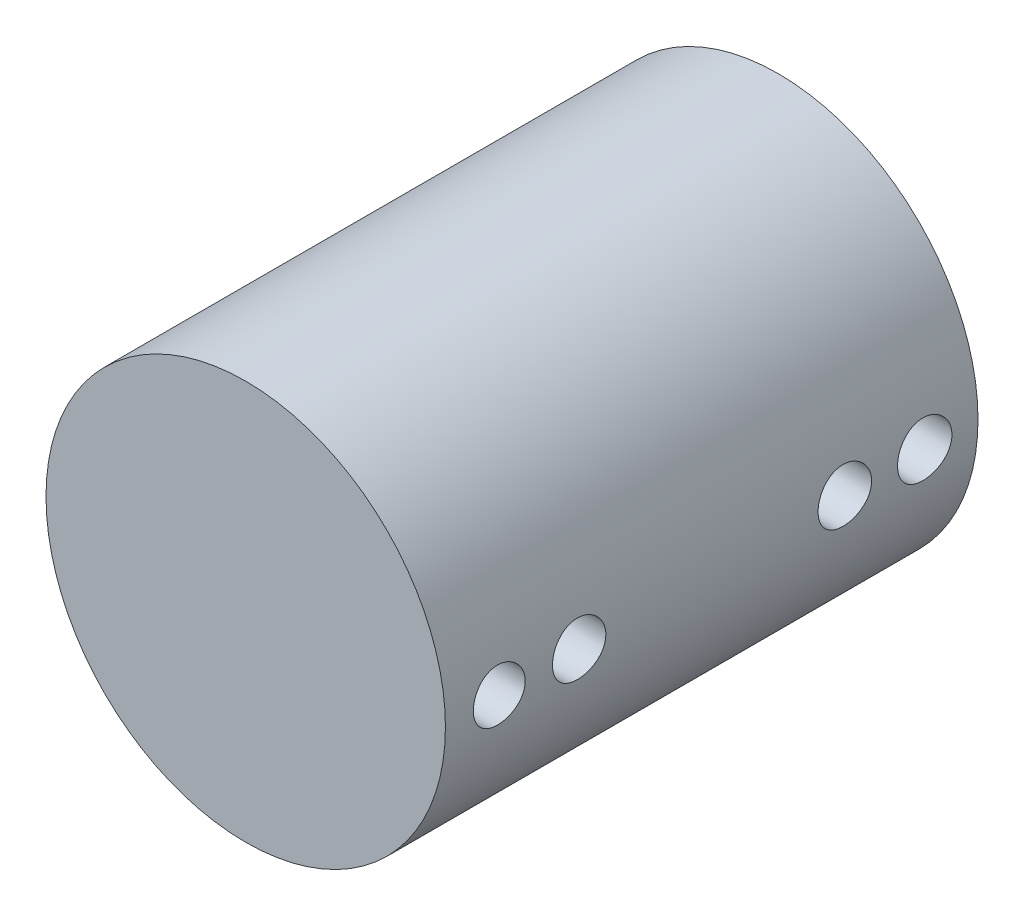
SolidWorks part; units mm, degrees
ref_plane "Front Plane" through (0, 0, 0) normal (0, 0, 1) x (1, 0, 0)
ref_plane "Top Plane" through (0, 0, 0) normal (0, 1, 0) x (1, 0, 0)
ref_plane "Right Plane" through (0, 0, 0) normal (1, 0, 0) x (0, 0, -1)
sketch "Sketch2" plane through (0, 0, 0) normal (0, 0, 1) x (1, 0, 0)
  circle A0 centre (0, 0) radius 19.05
extrude "Boss-Extrude1" add sketch "Sketch2" along normal blind 50.8
ref_plane "Plane1" through (-19.05, 0, 0) normal (-1, 0, 0) x (0, 0, 1)
sketch "Sketch3" plane through (-19.05, 0, 0) normal (-1, 0, 0) x (0, 0, 1)
  line L0 (0, 0) -> (50.7435, 0) construction
  circle A0 centre (5.08, 0) radius 2.5933
  circle A1 centre (12.7, 0) radius 2.5528
  circle A2 centre (45.6635, 0) radius 2.4772
  circle A3 centre (38.0435, 0) radius 2.546
  point P11 (0, 0)
  point P12 (0, 0)
  point P13 (0, 0)
  point P14 (0, 0)
  dimension "D1" = 12.7
  dimension "D2" = 12.7
  dimension "D3" = 5.08
  dimension "D4" = 5.08
extrude "Cut-Extrude1" cut sketch "Sketch3" against normal through all
